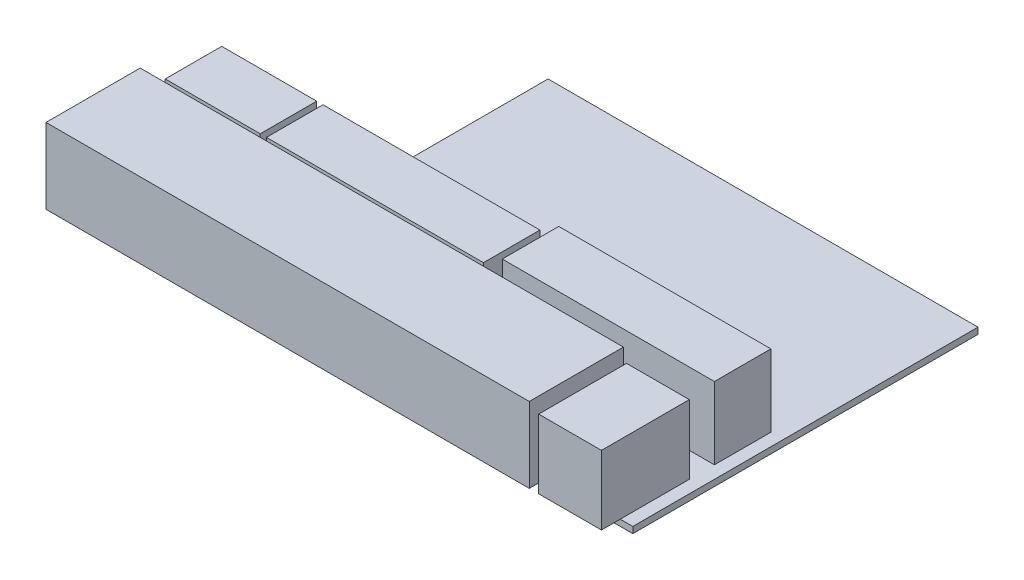
SolidWorks part; units mm, degrees
ref_plane "Front Plane" through (0, 0, 0) normal (0, 0, 1) x (1, 0, 0)
ref_plane "Top Plane" through (0, 0, 0) normal (0, 1, 0) x (1, 0, 0)
ref_plane "Right Plane" through (0, 0, 0) normal (1, 0, 0) x (0, 0, -1)
sketch "Sketch1" plane through (0, 0, 0) normal (0, 1, 0) x (1, 0, 0)
  line L0 (-46.967, -0.6277) -> (-21.967, -0.6277)
  line L1 (-21.967, 27.3723) -> (46.533, 27.3723)
  line L2 (-46.967, -0.6277) -> (-46.967, -27.6277)
  line L3 (-46.967, -27.6277) -> (46.533, -27.6277)
  line L4 (46.533, 27.3723) -> (46.533, -27.6277)
  line L5 (-21.967, 13.0423) -> (46.533, -27.6277) construction
  line L6 (-46.967, -27.6277) -> (46.533, 27.3723) construction
  line L7 (-21.967, -0.6277) -> (-21.967, 27.3723)
  point P4 (0, 0)
  dimension "D1" = 55
  dimension "D2" = 93.5
  dimension "D3" = 25
  dimension "D4" = 28
extrude "Boss-Extrude1" add sketch "Sketch1" along normal blind 1 contours L1 L4 L3 L2 L0 L7
sketch "Sketch2" plane through (0, 1, 0) normal (0, 1, 0) x (1, 0, 0)
  line L0 (-46.967, -0.6277) -> (-46.967, -27.6277) construction
  line L1 (-43.967, -15.6277) -> (33.033, -15.6277)
  line L2 (-43.967, -15.6277) -> (-43.967, -30.6277)
  line L3 (-43.967, -30.6277) -> (33.033, -30.6277)
  line L4 (33.033, -15.6277) -> (33.033, -30.6277)
  line L5 (-43.967, -15.6277) -> (33.033, -30.6277) construction
  line L6 (-43.967, -30.6277) -> (33.033, -15.6277) construction
  line L8 (-46.967, -27.6277) -> (46.533, -27.6277) construction
  point P4 (-5.467, -23.1277)
  dimension "D1" = 15
  dimension "D2" = 77
  dimension "D3" = 3
  dimension "D4" = 3
extrude "Boss-Extrude2" add sketch "Sketch2" along normal blind 12
sketch "Sketch3" plane through (0, 1, 0) normal (0, 1, 0) x (1, 0, 0)
  line L0 (46.533, 27.3723) -> (46.533, -27.6277) construction
  line L1 (34.533, -16.6277) -> (44.533, -16.6277)
  line L2 (34.533, -16.6277) -> (34.533, -30.6277)
  line L3 (34.533, -30.6277) -> (44.533, -30.6277)
  line L4 (44.533, -16.6277) -> (44.533, -30.6277)
  line L5 (34.533, -16.6277) -> (44.533, -30.6277) construction
  line L6 (34.533, -30.6277) -> (44.533, -16.6277) construction
  line L7 (-43.967, -30.6277) -> (33.033, -30.6277) construction
  line L8 (33.033, -15.6277) -> (-43.967, -15.6277) construction
  point P4 (39.533, -23.6277)
  dimension "D1" = 10
  dimension "D2" = 2
  dimension "D3" = 1
extrude "Boss-Extrude3" add sketch "Sketch3" along normal blind 11
sketch "Sketch4" plane through (0, 1, 0) normal (0, 1, 0) x (1, 0, 0)
  line L0 (46.533, -27.6277) -> (46.533, -3.6277) construction
  line L1 (46.533, 27.3723) -> (46.533, -27.6277) construction
  line L2 (46.533, -3.6277) -> (-46.967, -3.6277) construction
  line L3 (-46.967, -0.6277) -> (-46.967, -27.6277) construction
  line L4 (-46.967, -3.6277) -> (-46.967, -27.6277) construction
  line L5 (-46.967, -27.6277) -> (-46.967, -14.6277) construction
  line L6 (-40.967, -14.6277) -> (-40.967, -5.6277)
  line L7 (-40.967, -5.6277) -> (-25.8331, -5.6277)
  line L8 (-25.8331, -5.6277) -> (-25.8331, -14.6277)
  line L9 (-25.8331, -14.6277) -> (-40.967, -14.6277)
  line L10 (-24.8331, -14.6277) -> (9.734, -14.6277)
  line L11 (9.734, -14.6277) -> (9.734, -5.6277)
  line L12 (9.734, -5.6277) -> (-24.8331, -5.6277)
  line L13 (-24.8331, -5.6277) -> (-24.8331, -14.6277)
  line L14 (46.533, -3.6277) -> (9.533, -3.6277) construction
  line L15 (44.533, -27.6277) -> (44.533, -16.6277) construction
  line L16 (10.734, -3.6277) -> (44.533, -3.6277)
  line L17 (10.734, -3.6277) -> (10.734, -12.6277)
  line L18 (10.734, -12.6277) -> (44.533, -12.6277)
  line L19 (44.533, -3.6277) -> (44.533, -12.6277)
  point P27 (0, 0)
  dimension "D1" = 24
  dimension "D2" = 13
  dimension "D3" = 37
  dimension "D4" = 1
  dimension "D5" = 1
  dimension "D6" = 3
  dimension "D7" = 2
  dimension "D8" = 9
extrude "Boss-Extrude4" add sketch "Sketch4" along normal blind 11.5 separate body
